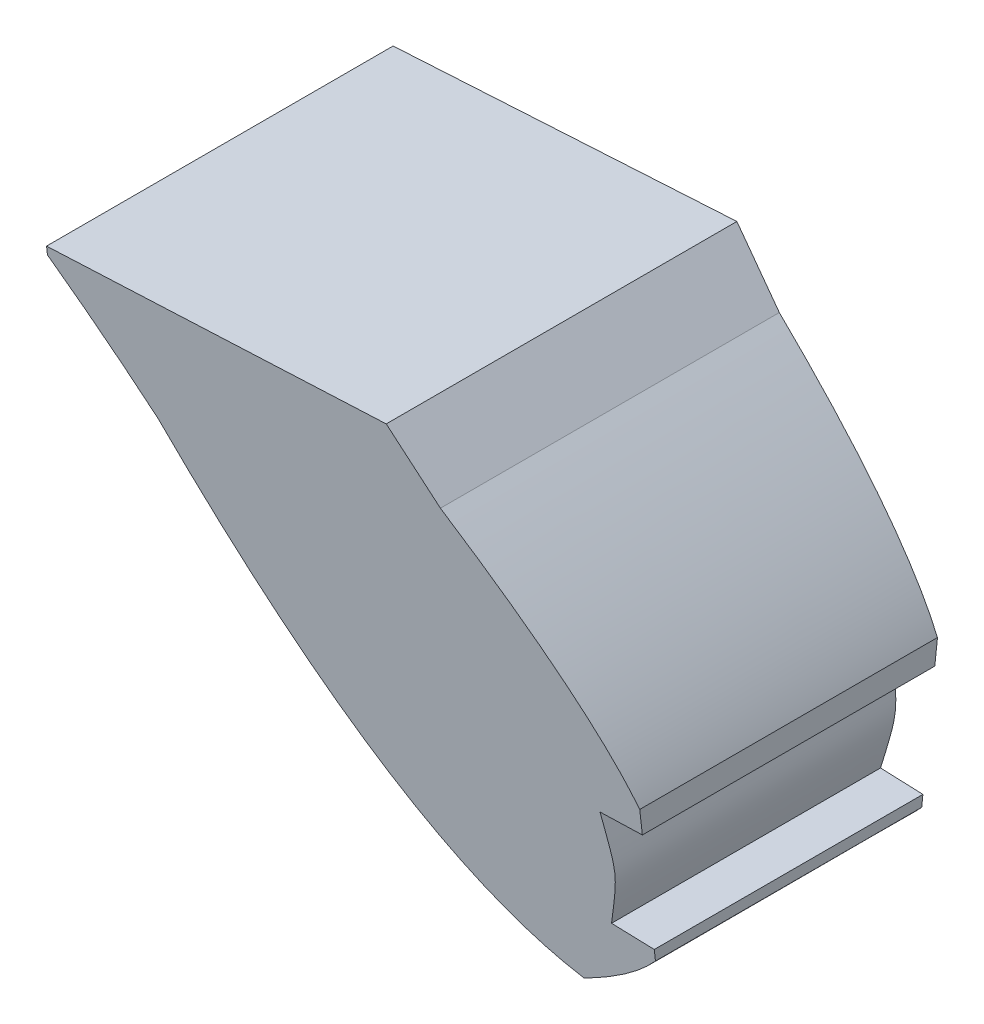
SolidWorks part; units mm, degrees
ref_plane "Alzado" through (0, 0, 0) normal (0, 0, 1) x (1, 0, 0)
ref_plane "Planta" through (0, 0, 0) normal (0, 1, 0) x (1, 0, 0)
ref_plane "Vista lateral" through (0, 0, 0) normal (1, 0, 0) x (0, 0, -1)
sketch "Croquis1" plane through (0, 0, 0) normal (0, 0, 1) x (1, 0, 0)
  line L0 (-8.9818, 12.6082) -> (-23.0359, 11.8716) construction
  line L1 (-8.9818, 12.6082) -> (-23.0359, 11.8716)
  line L2 (-8.9818, 12.6082) -> (-23.0359, 11.8716) construction
  line L4 (-8.9818, 12.6082) -> (-23.0359, 11.8716)
  line L6 (-1.3949, 1.9763) -> (0.3551, 2.2848) construction
  line L7 (-1.3949, 1.9763) -> (0.3551, 2.2848)
  line L8 (0.3551, 2.2848) -> (0.3551, 2.8423) construction
  line L9 (0.3551, 2.2848) -> (0.3551, 3.0015)
  line L10 (0.3551, -2.2848) -> (-1.3949, -2.2237) construction
  line L11 (0.3551, -2.2848) -> (-1.3949, -2.2237)
  line L12 (0.3551, 2.2848) -> (0.3551, -2.2848) construction
  line L13 (0.3551, -2.2848) -> (0.3551, -2.7233)
  line L14 (-8.9818, 12.6082) -> (-6.9949, 10.4774)
  line L15 (-23.0359, 11.5401) -> (-23.0359, 11.8716) construction
  line L16 (-23.0359, 11.5401) -> (-23.0359, 11.8716)
  arc A0 (-18.9452, 7.5409) -> (-23.0359, 11.5401) centre (-69.8841, -40.4718) ccw construction
  arc A1 (-18.9452, 7.5409) -> (-23.0359, 11.5401) centre (-69.8841, -40.4718) ccw
  spline S1 degree 2 poles (-828.7061, 3922.2202) (545.889, -3962.7836) (-262.0834, 3982.5902) knots 0.462185 0.462185 0.462185 0.537731 0.537731 0.537731 weights 1 1 1 only from (-18.9452, 7.5409) to (-2.8466, -5.0591) construction
  spline S2 degree 2 poles (-18.9452, 7.5409) (-10.215, -3.6976) (-2.8466, -5.0591) knots 0.497667 0.497667 0.497667 0.499554 0.499554 0.499554 weights 1 1 1
  spline S3 degree 2 poles (-3804.8689, 1232.5771) (3762.9122, -1369.6643) (-3716.5752, 1504.852) knots 0.462212 0.462212 0.462212 0.537836 0.537836 0.537836 weights 1 1 1 only from (0.3551, 3.0015) to (-6.9949, 10.4774) construction
  spline S4 degree 2 poles (0.3551, 3.0015) (-1.4487, 6.0584) (-6.9949, 10.4774) knots 0.500821 0.500821 0.500821 0.502013 0.502013 0.502013 weights 1 1 1
  spline S5 degree 2 poles (-1.3949, -2.2237) (-0.9075, -0.1237) (-1.3949, 1.9763) knots 0 0 0 1 1 1 weights 1 3.231801 1 construction
  spline S6 degree 2 poles (-1.3949, -2.2237) (-0.9075, -0.1237) (-1.3949, 1.9763) knots 0 0 0 1 1 1 weights 1 3.231801 1
  spline S7 degree 2 poles (-3997.263, 185.0077) (3984.2333, -348.7483) (-3965.0625, 511.2595) knots 0.462205 0.462205 0.462205 0.537778 0.537778 0.537778 weights 1 1 1 only from (-2.8466, -5.0591) to (0.3551, -2.7233) construction
  spline S8 degree 2 poles (-2.8466, -5.0591) (-0.7424, -3.9352) (0.3551, -2.7233) knots 0.498812 0.498812 0.498812 0.499413 0.499413 0.499413 weights 1 1 1
extrude "Saliente-Extruir1" add sketch "Croquis1" along normal mid plane 14.42 contours S2 S8 L13 L11 S6 L7 L9 S4 L14 L1 L16 A1
sketch "Croquis3" plane through (0, 0, 0) normal (0, 0, 1) x (1, 0, 0)
  line L0 (-6.742, 0) -> (0, 0) construction
  line L1 (-1.8181, 2) -> (-1.7771, 2.0103) construction
  line L3 (-1.8181, 2) -> (-0.1689, 2.4155) construction
  line L4 (-1.8181, 2) -> (0.3551, 3.0015)
  line L5 (0.3551, 3.0015) -> (0.3551, 0)
  line L6 (-1.9123, -2.1803) -> (0.3551, -2.2848)
  line L7 (0.3551, -2.2848) -> (0.3551, 0)
  parabola Q0 (-1.9123, -2.1803) -> (-1.8181, 2) focus (-3.3181, 0) apex (-1.3181, 0)
  dimension "D1" = 2
  dimension "D2" = 2
extrude "Cortar-Extruir1" [suppressed] cut sketch "Croquis3" against normal through all both and the other way through all
sketch "Croquis4" plane through (0, 0, 0) normal (0, 0, 1) x (1, 0, 0)
  line L0 (-1.3949, 1.9763) -> (0.3551, 2.2848) construction
  line L1 (-1.3949, 1.9763) -> (0.3551, 2.2848)
  line L2 (0.3551, 2.2848) -> (0.3551, 3.0015) construction
  line L3 (0.3551, 2.0374) -> (0.3551, 2.2848)
  line L4 (-1.3949, 1.9763) -> (0.3551, 2.0374)
  line L5 (0, 0) -> (-3.4665, 0) construction
  dimension "D1" = 2
extrude "Saliente-Extruir2" add sketch "Croquis4" along normal through all and the other way through all
sketch "Croquis7" plane through (0, 0, 0) normal (0, 0, 1) x (1, 0, 0)
  line L0 (0, 0) -> (-15.3945, 3.3171) construction
  line L1 (-17.3963, 18.9371) -> (-15.3945, 3.3171) construction
  line L2 (-15.3945, 3.3171) -> (-9.9316, -2.6296) construction
  line L3 (-15.3945, 3.3171) -> (-10.2385, 8.0535) construction
  line L4 (-17.3963, 18.9371) -> (-16.5429, 12.2783) construction
  line L5 (0, 0) -> (-1.3461, -2.2254) construction
  line L6 (-69.8841, 29.5282) -> (-81.9382, 42.5765) construction
  line L7 (-69.8841, 29.5282) -> (-20.9497, 29.5282) construction
  line L8 (-17.8101, 13.1658) -> (-25.5429, 13.1658)
  line L9 (-18.2059, 7.0951) -> (-21.9246, 11.9299) construction
  line L10 (0.3551, -2.5) -> (-2.4497, -2.0473)
  line L11 (-1.3461, -2.2254) -> (-2.0075, -3.6222) construction
  line L12 (-1.3461, -2.2254) -> (-1.4547, -2.8987) construction
  line L13 (-1.3461, -2.2254) -> (-1.2286, -1.4976) construction
  line L14 (0.3551, -2.2848) -> (0.3551, -2.7233) construction
  line L15 (0.3551, -2.2848) -> (-1.3949, -2.2237) construction
  line L16 (-2.0075, -3.6222) -> (-3.0629, -5.8512) construction
  line L17 (-2.6331, -4.9434) -> (-3.7044, -5.5324) construction
  line L18 (-2.6331, -4.9434) -> (-3.2248, -3.867) construction
  line L19 (-2.6331, -4.9434) -> (-2.2174, -6.1341) construction
  line L20 (-4.0838, -4.7637) -> (-1.6363, -5.0668) construction
  line L21 (-4.0838, -4.7637) -> (-0.036, -5.9454) construction
  line L22 (-4.0838, -4.7637) -> (-3.7621, -3.6616) construction
  line L23 (-4.0838, -4.7637) -> (-6.31, -3.7023) construction
  line L24 (-6.31, -3.7023) -> (-8.69, -2.5677) construction
  line L25 (-8.69, -2.5677) -> (-6.8421, -3.7725) construction
  line L26 (-8.69, -2.5677) -> (-7.9481, -1.4297) construction
  line L27 (-10.6884, -0.8477) -> (-8.69, -2.5677) construction
  line L28 (-10.6884, -0.8477) -> (-14.8546, 2.738) construction
  line L29 (-14.8546, 2.738) -> (-14.5337, 2.3989) construction
  line L30 (-14.8546, 2.738) -> (-14.6199, 2.9602) construction
  line L31 (-18.2059, 7.0951) -> (-14.8546, 2.738) construction
  line L32 (-8.9818, 12.6082) -> (-23.0359, 11.8716) construction
  line L33 (-8.9818, 12.6082) -> (-23.0359, 11.8716)
  line L34 (-21.9246, 11.9299) -> (-21.9826, 13.0367) construction
  line L35 (-21.9246, 11.9299) -> (-23.4156, 13.0367) construction
  arc A0 (-18.9452, 7.5409) -> (-23.0359, 11.5401) centre (-69.8841, -40.4718) ccw construction
  spline S0 degree 2 poles (-654.4568, 2937.5195) (409.3679, -2972.9237) (-163.476, 2987.5518) knots 0.467242 0.467242 0.467242 0.532662 0.532662 0.532662 weights 1 1 1 only from (-18.9452, 7.5409) to (-2.8466, -5.0591) construction
  spline S1 degree 2 poles (-18.6263, 7.1332) (-10.0803, -3.7225) (-2.8466, -5.0591) knots 0.497702 0.497702 0.497702 0.499554 0.499554 0.499554 weights 1 1 1 construction
  spline S3 degree 2 poles (-2999.4042, 119.7504) (2988.2948, -261.6206) (-2971.0465, 402.239) knots 0.467267 0.467267 0.467267 0.532713 0.532713 0.532713 weights 1 1 1 only from (-2.8466, -5.0591) to (0.3551, -2.7233) construction
  spline S4 degree 2 poles (-2.8466, -5.0591) (-2.7385, -5.0013) (-2.6331, -4.9434) knots 0.498812 0.498812 0.498812 0.498843 0.498843 0.498843 weights 1 1 1
  dimension "D1" = 2.5
  dimension "D2" = 22
  dimension "D3" = 16.17
  dimension "D4" = 54.138
  dimension "D5" = 34.566
  dimension "D6" = 50.413
sketch "Croquis6" plane through (0, 0, 0) normal (1, 0, 0) x (0, 0, -1)
  line L0 (7.21, 12.6082) -> (7.21, 10.4774) construction
  line L1 (7.21, 12.6082) -> (7.21, -5.0591)
  line L2 (-7.21, 12.6082) -> (-7.21, 10.4774) construction
  line L3 (-7.21, 12.6082) -> (-7.21, -5.0591)
  line L4 (-7.21, -5.0591) -> (7.21, -5.0591) construction
  line L5 (-7.21, -5.0591) -> (-5.21, -5.0591)
  line L6 (7.21, 12.6082) -> (5.21, -5.0591)
  line L7 (-7.21, 12.6082) -> (-5.21, -5.0591)
  line L8 (5.21, -5.0591) -> (7.21, -5.0591)
  dimension "D1" = 2
  dimension "D2" = 2
extrude "Cortar-Extruir2" cut sketch "Croquis6" against normal through all and the other way through all
